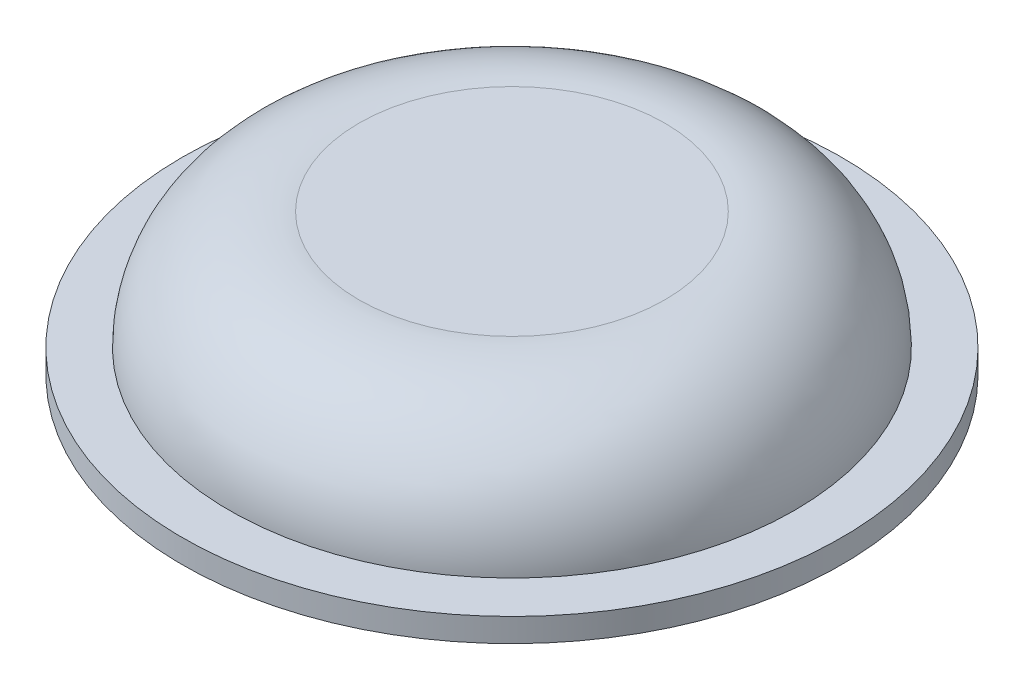
SolidWorks part; units mm, degrees
ref_plane "Front Plane" through (0, 0, 0) normal (0, 0, 1) x (1, 0, 0)
ref_plane "Top Plane" through (0, 0, 0) normal (0, 1, 0) x (1, 0, 0)
ref_plane "Right Plane" through (0, 0, 0) normal (1, 0, 0) x (0, 0, -1)
sketch "Sketch1" plane through (0, 0, 0) normal (0, 0, 1) x (1, 0, 0)
  line L0 (-35.56, 0) -> (-35.56, 2.54)
  line L1 (-35.56, 2.54) -> (-30.48, 2.54)
  line L3 (-26.67, 0) -> (-35.56, 0)
  line L4 (0, 6.4276) -> (-2.54, 6.4276)
  line L6 (-26.67, 7.4736) -> (-26.67, 0)
  line L7 (0, 6.4276) -> (0, 0) construction
  line L8 (-16.51, 15.24) -> (0, 15.24)
  line L9 (0, 15.24) -> (0, 6.4276)
  line L10 (-2.54, 6.4276) -> (-2.54, 11.43)
  line L11 (-2.54, 11.43) -> (-22.7591, 11.43)
  arc A0 (-30.48, 2.54) -> (-16.51, 15.24) centre (-17.7223, 2.54) cw
  arc A2 (-22.7591, 11.43) -> (-26.67, 7.4736) centre (-17.7223, 2.54) ccw
  point P8 (-11.9914, 22.4687)
  dimension "D7" = 2.54
  dimension "D1" = 2.54
  dimension "D2" = 35.56
  dimension "D3" = 5.08
  dimension "D4" = 3.81
  dimension "D5" = 2.54
  dimension "D6" = 16.51
  dimension "D8" = 15.24
  dimension "D9" = 3.81
revolve "Revolve1" add sketch "Sketch1" angle 360 about L9
